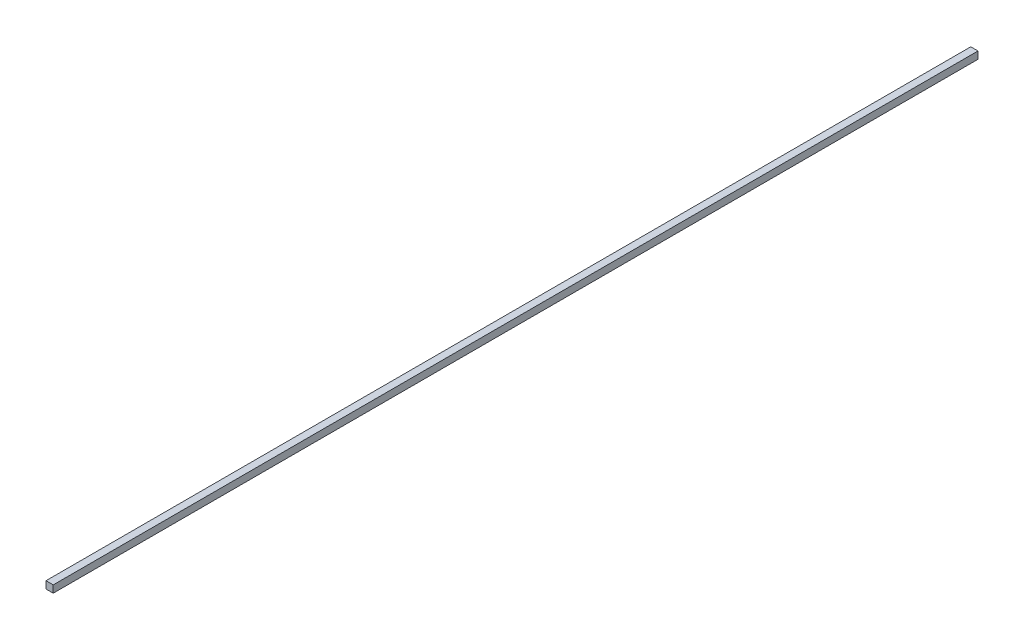
SolidWorks part; units mm, degrees
other "Imported1" parameters "D1"=113.1112, "Length"=113.1112, "Width"=2.3813, "D2"=51.1131, "Height"=2.3813
ref_plane "Front Plane" through (0, 0, 0) normal (0, 0, 1) x (1, 0, 0)
ref_plane "Top Plane" through (0, 0, 0) normal (0, 1, 0) x (1, 0, 0)
ref_plane "Right Plane" through (0, 0, 0) normal (1, 0, 0) x (0, 0, -1)
sketch "Sketch1" plane through (0, 0, 0) normal (0, 0, 1) x (1, 0, 0)
  line L0 (-1.1906, 1.1906) -> (1.1906, -1.1906) construction
  line L1 (-1.1906, 1.1906) -> (1.1906, 1.1906) construction
  line L2 (-1.1906, 1.1906) -> (-1.1906, -1.1906) construction
  line L3 (-1.1906, -1.1906) -> (1.1906, -1.1906) construction
  line L4 (1.1906, 1.1906) -> (1.1906, -1.1906) construction
sketch "Sketch2" plane through (0, 0, 0) normal (1, 0, 0) x (0, 0, -1)
  line L0 (152.4, 0) -> (-152.4, 0) construction
  line L1 (-152.4, 0) -> (-152.4, 1.1906) construction
  line L2 (-152.4, 1.1906) -> (152.4, 1.1906) construction
  line L3 (152.4, 1.1906) -> (152.4, 0) construction
  line L4 (-145.2562, 0) -> (-145.2562, 1.1906) construction
  line L5 (-145.2562, 0) -> (145.2562, 0) construction
  line L6 (145.2562, 0) -> (145.2562, 1.1906) construction
  point P2 (0, 1.1906)
  dimension "Length" = 304.8
  dimension "D1" = 7.1437
sketch "Sketch3" plane through (0, 0, 0) normal (0, 0, 1) x (1, 0, 0)
  line L0 (-1.1906, 1.1906) -> (1.1906, 1.1906)
  line L1 (1.1906, 1.1906) -> (1.1906, -1.1906)
  line L2 (1.1906, -1.1906) -> (-1.1906, -1.1906)
  line L3 (-1.1906, -1.1906) -> (-1.1906, 1.1906)
extrude "Boss-Extrude1" add sketch "Sketch3" along normal up to vertex (152.4 mm away) and the other way up to vertex (152.4 mm away) up to point (0, 0, 152.4) other way up to point (0, 0, -152.4)
equation "\"D1@Sketch2\"=\"Height@Sketch1\"*3"
